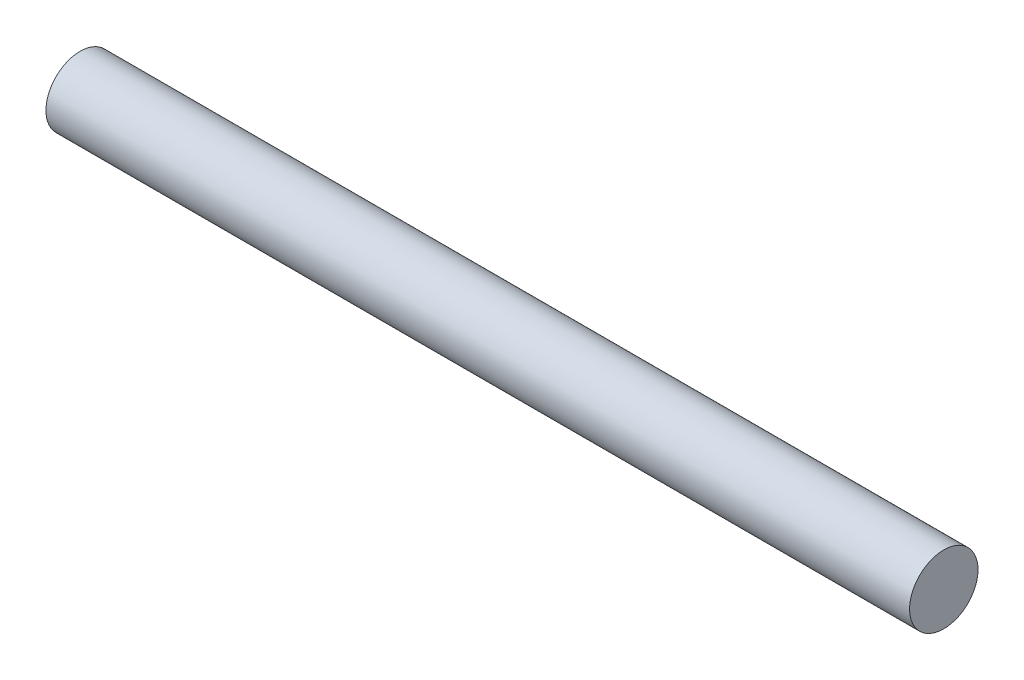
SolidWorks part; units mm, degrees
ref_plane "Plan de face" through (0, 0, 0) normal (0, 0, 1) x (1, 0, 0)
ref_plane "Plan de dessus" through (0, 0, 0) normal (0, 1, 0) x (1, 0, 0)
ref_plane "Plan de droite" through (0, 0, 0) normal (1, 0, 0) x (0, 0, -1)
sketch "Esquisse1" plane through (0, 0, 0) normal (1, 0, 0) x (0, 0, -1)
  circle A0 centre (-12.4719, -56.3241) radius 4
  dimension "D1" = 8
extrude "Boss.-Extru.1" add sketch "Esquisse1" along normal blind 101
